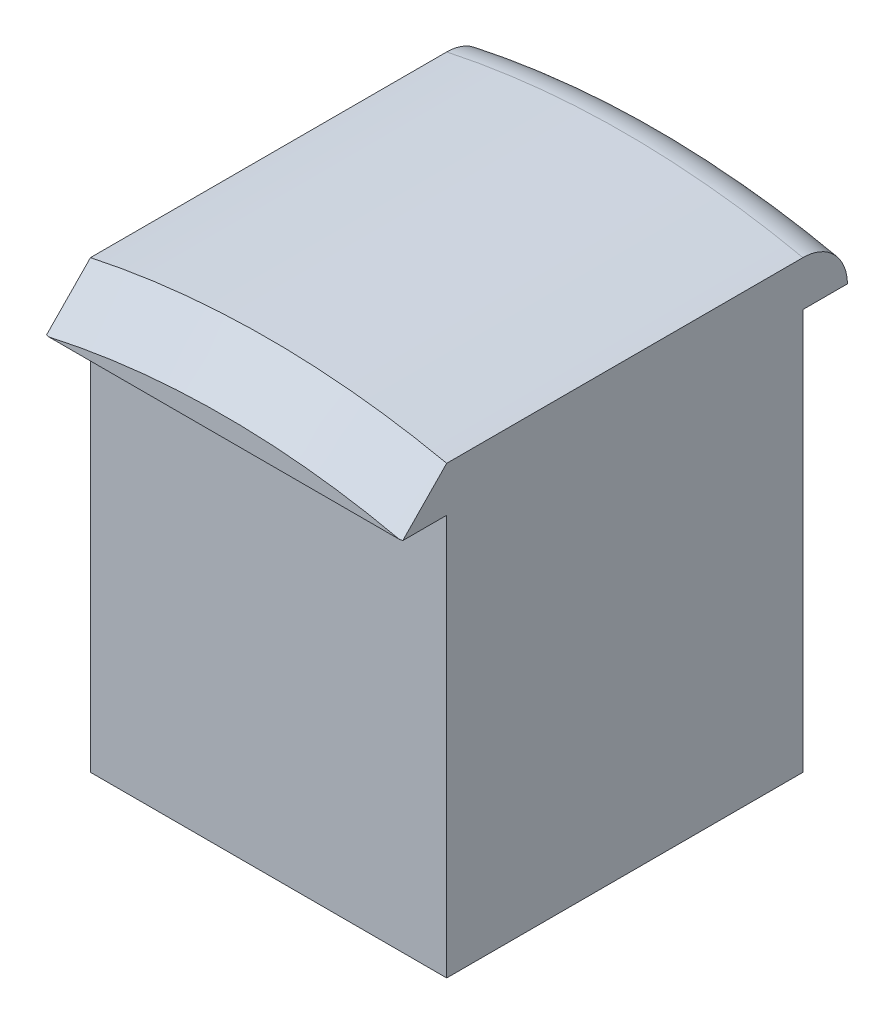
SolidWorks part; units mm, degrees
ref_plane "Alzado" through (0, 0, 0) normal (0, 0, 1) x (1, 0, 0)
ref_plane "Planta" through (0, 0, 0) normal (0, 1, 0) x (1, 0, 0)
ref_plane "Vista lateral" through (0, 0, 0) normal (1, 0, 0) x (0, 0, -1)
sketch "Croquis1" plane through (0, 0, 0) normal (0, 0, 1) x (1, 0, 0)
  line L9 (-50.7946, 121.0777) -> (-50.7946, 76.8462)
  line L10 (-50.7946, 76.8462) -> (-10.7946, 76.8462)
  line L11 (-10.7946, 76.8462) -> (-10.7946, 121.0777)
  line L14 (-50.7946, 121.0777) -> (-50.7946, 126.8971)
  line L15 (-10.7946, 121.0777) -> (-10.7946, 126.8971)
  arc A1 (-10.7946, 126.8971) -> (-50.7946, 126.8971) centre (-30.7946, 34.0262) ccw
  point P1 (-30.7946, 129.0262)
  dimension "D1" = 52.18
  dimension "D9" = 190
  dimension "D3" = 40
  dimension "D6" = 20
extrude "Saliente-Extruir1" add sketch "Croquis1" along normal blind 50
sketch "Croquis4" plane through (-50.7946, 0, 0) normal (-1, 0, 0) x (0, 0, 1)
  line L0 (0, 76.8462) -> (0, 126.8971) construction
  line L1 (0, 121.8462) -> (5, 121.8462)
  line L2 (0, 121.8462) -> (0, 76.8462)
  line L3 (0, 76.8462) -> (5, 76.8462)
  line L4 (5, 121.8462) -> (5, 76.8462)
  line L5 (50, 76.8462) -> (0, 76.8462) construction
  line L6 (50, 76.8462) -> (50, 126.8971) construction
  line L7 (50, 121.8462) -> (45, 121.8462)
  line L8 (50, 121.8462) -> (50, 76.8462)
  line L9 (50, 76.8462) -> (45, 76.8462)
  line L10 (45, 121.8462) -> (45, 76.8462)
  dimension "D1" = 5
  dimension "D2" = 5
  dimension "D3" = 45
  dimension "D4" = 45
extrude "Cortar-Extruir3" cut sketch "Croquis4" against normal blind 50
sketch "Croquis5" plane through (0, 0, 5) normal (0, 0, -1) x (-1, 0, 0)
  line L0 (10.7946, 121.8462) -> (50.7946, 121.8462) construction
  line L1 (12.7946, 121.8462) -> (48.7946, 121.8462)
  line L2 (12.7946, 121.8462) -> (12.7946, 78.8462)
  line L3 (12.7946, 78.8462) -> (48.7946, 78.8462)
  line L4 (48.7946, 121.8462) -> (48.7946, 78.8462)
  line L5 (10.7946, 76.8462) -> (10.7946, 121.8462) construction
  line L6 (50.7946, 76.8462) -> (50.7946, 121.8462) construction
  line L7 (10.7946, 76.8462) -> (50.7946, 76.8462) construction
  dimension "D1" = 2
  dimension "D2" = 2
  dimension "D3" = 2
extrude "Cortar-Extruir4" cut sketch "Croquis5" against normal blind 38
fillet "Redondeo1" radius 5 1 edges at (-30.7946, 129.0262, 0)
chamfer "Chaflán1" distance 5 angle 45 1 edges at (-30.7946, 129.0262, 50)
